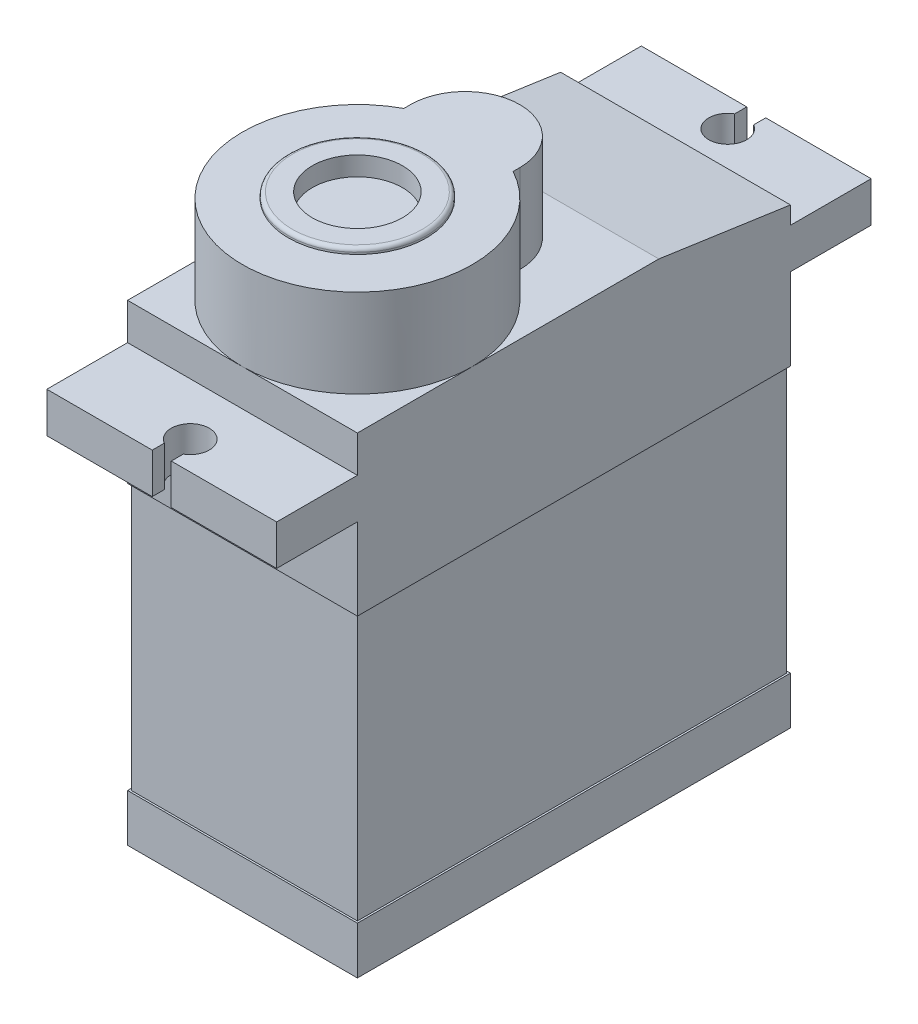
SolidWorks part; units mm, degrees
ref_plane "Front Plane" through (0, 0, 0) normal (0, 0, 1) x (1, 0, 0)
ref_plane "Top Plane" through (0, 0, 0) normal (0, 1, 0) x (1, 0, 0)
ref_plane "Right Plane" through (0, 0, 0) normal (1, 0, 0) x (0, 0, -1)
sketch "Sketch1" plane through (0, 0, 0) normal (0, 1, 0) x (1, 0, 0)
  line L1 (6.05, -11.4) -> (-6.05, -11.4)
  line L2 (6.05, -11.4) -> (6.05, 11.4)
  line L3 (6.05, 11.4) -> (-6.05, 11.4)
  line L4 (-6.05, -11.4) -> (-6.05, 11.4)
  line L5 (6.05, -11.4) -> (-6.05, 11.4) construction
  line L6 (6.05, 11.4) -> (-6.05, -11.4) construction
  point P0 (0, 0)
  dimension "D1" = 22.8
  dimension "D2" = 12.1
extrude "Boss-Extrude1" add sketch "Sketch1" along normal blind 24.85
sketch "Sketch2" plane through (-6.05, 0, 0) normal (-1, 0, 0) x (0, 0, 1)
  line L1 (-11.4, 23.85) -> (-4.4718, 24.85)
  line L2 (-11.4, 24.85) -> (-11.4, 0) construction
  line L3 (-11.4, 24.85) -> (11.4, 24.85) construction
  line L4 (-4.4718, 24.85) -> (11.4, 24.85)
  line L5 (11.4, 24.85) -> (11.4, 0)
  line L6 (11.4, 0) -> (-11.4, 0)
  line L7 (-11.4, 0) -> (-11.4, 23.85)
  dimension "D1" = 23.85
  dimension "D2" = 7
extrude "Cut-Extrude1" cut sketch "Sketch2" against normal blind 24.85 flip side to cut
sketch "Sketch3" plane through (0, 24.85, 0) normal (0, 1, 0) x (1, 0, 0)
  line L0 (-6.05, -11.4) -> (6.05, -11.4) construction
  line L1 (-1.2801, 3.2) -> (1.4091, 3.2) construction
  line L2 (2.875, 0.325) -> (2.875, -0.0268)
  line L3 (-2.875, 0.325) -> (-2.875, -0.0268)
  line L4 (0, 3.2) -> (0, -11.4) construction
  line L5 (-6.05, 4.4718) -> (-6.05, -11.4) construction
  line L6 (6.05, -11.4) -> (6.05, 4.4718) construction
  circle A0 centre (0, -5.35) radius 6.05
  circle A1 centre (0, 0.325) radius 2.875
  dimension "D2" = 5.75
  dimension "D1" = 14.6
extrude "Boss-Extrude2" add sketch "Sketch3" along normal offset from surface (4.65 mm away) 29.5 contours A1 A0 | A1 A0 L2 | A1 L3 A0 | A0 A1 | A0 A1 up to face at (0, 0, 0)
sketch "Sketch4" plane through (0, 0, 0) normal (0, 1, 0) x (1, 0, 0)
  line L0 (-6.05, 11.4) -> (-6.05, -11.4) construction
  line L1 (-6.05, 0) -> (6.05, 0) construction
  line L2 (6.05, -5.35) -> (6.05, 4.4718) construction
  line L3 (0, 15.15) -> (0, 15.65) construction
  line L4 (-6.05, 11.4) -> (6.05, 11.4)
  line L5 (-6.05, 11.4) -> (-6.05, 15.65)
  line L6 (-6.05, 15.65) -> (6.05, 15.65)
  line L7 (6.05, 11.4) -> (6.05, 15.65)
  line L8 (-6.05, -11.4) -> (6.05, -11.4)
  line L9 (-6.05, -11.4) -> (-6.05, -15.65)
  line L10 (-6.05, -15.65) -> (6.05, -15.65)
  line L11 (6.05, -11.4) -> (6.05, -15.65)
  line L12 (-0.5, 15.65) -> (-0.5, 15.016)
  line L13 (0.5, 15.016) -> (0.5, 15.65)
  line L14 (6.05, 4.4718) -> (6.05, 11.4) construction
  line L15 (6.05, -11.4) -> (6.05, -5.35) construction
  line L16 (0.5, -15.016) -> (0.5, -15.65)
  line L17 (-0.5, -15.65) -> (-0.5, -15.016)
  circle A0 centre (0, 14.15) radius 1
  circle A1 centre (0, -14.15) radius 1
  dimension "D2" = 2
  dimension "D1" = 4.25
  dimension "D3" = 1.5
  dimension "D4" = 0.5
extrude "Boss-Extrude3" add sketch "Sketch4" along normal blind 2.12 from offset 20.8 contours A0 L12 L6 L5 L4 L7 L13 | L17 A1 L16 L10 L11 L8 L9
sketch "Sketch6" plane through (0, 0, 0) normal (0, -1, 0) x (1, 0, 0)
  line L0 (5.95, 11.3) -> (-5.95, 11.3)
  line L1 (-5.95, 11.3) -> (-5.95, -11.3)
  line L2 (-5.95, -11.3) -> (5.95, -11.3)
  line L3 (5.95, -11.3) -> (5.95, 11.3)
  line L4 (-6.05, 11.4) -> (-6.05, -11.4)
  line L5 (-6.05, -11.4) -> (6.05, -11.4)
  line L6 (6.05, -11.4) -> (6.05, 11.4)
  line L7 (6.05, 11.4) -> (-6.05, 11.4)
  line L8 (-6.05, 11.4) -> (-6.05, -11.4)
  line L9 (-6.05, -11.4) -> (6.05, -11.4)
  line L10 (6.05, -11.4) -> (6.05, 11.4)
  line L11 (6.05, 11.4) -> (-6.05, 11.4)
  dimension "D1" = 0
  dimension "D2" = 0.1
extrude "Cut-Extrude2" cut sketch "Sketch6" against normal blind 14 from offset 2.5 offset against normal yes
sketch "Sketch7" plane through (0, 24.9751, -3.6048) normal (0, 0.9897, -0.1429) x (1, 0, 0)
  line L0 (-20.8911, -66.3638) -> (-215.5578, -66.3638) construction
sketch "Sketch8" plane through (0, 29.5, 0) normal (0, 1, 0) x (1, 0, 0)
  circle A0 centre (0, -5.35) radius 3.625
  dimension "D1" = 7.25
extrude "Boss-Extrude5" add sketch "Sketch8" along normal blind 0.3
fillet "Fillet1" radius 0.2 1 edges at (0, 29.8, 8.975)
sketch "Sketch9" plane through (0, 29.8, 0) normal (0, 1, 0) x (1, 0, 0)
  circle A0 centre (0, -5.35) radius 2.375
  dimension "D1" = 4.75
extrude "Cut-Extrude3" cut sketch "Sketch9" against normal blind 1
